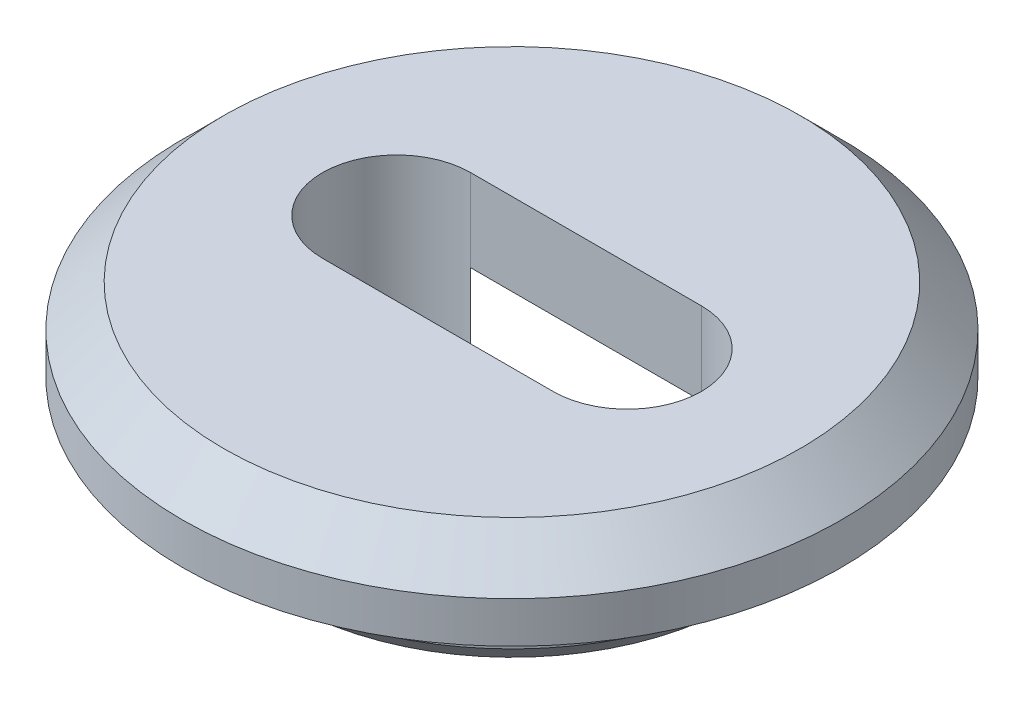
SolidWorks part; units mm, degrees
ref_plane "Front Plane" through (0, 0, 0) normal (0, 0, 1) x (1, 0, 0)
ref_plane "Top Plane" through (0, 0, 0) normal (0, 1, 0) x (1, 0, 0)
ref_plane "Right Plane" through (0, 0, 0) normal (1, 0, 0) x (0, 0, -1)
sketch "Sketch1" plane through (0, 0, 0) normal (0, 0, 1) x (1, 0, 0)
  line L0 (0, 0) -> (-8, 0)
  line L1 (-8, 0) -> (-8, -2)
  line L2 (-8, -2) -> (-6.1, -2)
  line L3 (-6.1, -2) -> (-6.1, -4)
  line L4 (-6.1, -4) -> (0, -4)
  line L5 (0, -4) -> (0, 0)
  line L6 (0, 0) -> (0, -10.029) construction
  dimension "D1" = 12.2
  dimension "D2" = 16
  dimension "D3" = 2
  dimension "D4" = 2
revolve "Revolve1" add sketch "Sketch1" angle 360 about L6
sketch "Sketch3" plane through (0, 0, 0) normal (0, 1, 0) x (1, 0, 0)
  line L0 (-2.8, 0) -> (2.8, 0) construction
  line L1 (-2.8, 1.8) -> (2.8, 1.8)
  line L2 (-2.8, -1.8) -> (2.8, -1.8)
  arc A0 (-2.8, 1.8) -> (-2.8, -1.8) centre (-2.8, 0) ccw
  arc A1 (2.8, -1.8) -> (2.8, 1.8) centre (2.8, 0) ccw
  point P2 (0, 0)
  dimension "D2" = 9.2
  dimension "D1" = 3.6
extrude "Cut-Extrude1" cut sketch "Sketch3" against normal through all
sketch "Sketch4" plane through (0, -4, 0) normal (0, -1, 0) x (1, 0, 0)
  line L0 (2.8, -1.8) -> (-2.8, -1.8) construction
  line L1 (-10.0418, -1.8) -> (11.1634, -1.8)
  line L2 (-10.0418, -1.8) -> (-10.0418, -3.6)
  line L3 (-10.0418, -3.6) -> (11.1634, -3.6)
  line L4 (11.1634, -1.8) -> (11.1634, -3.6)
  dimension "D1" = 1.8
extrude "Cut-Extrude2" cut sketch "Sketch4" against normal blind 2
sketch "Sketch5" plane through (0, -4, 0) normal (0, -1, 0) x (1, 0, 0)
  line L1 (-10.2288, -2.1496) -> (10.1665, -2.1496)
  line L2 (-10.2288, -2.1496) -> (-10.2288, -7.7988)
  line L3 (-10.2288, -7.7988) -> (10.1665, -7.7988)
  line L4 (10.1665, -2.1496) -> (10.1665, -7.7988)
extrude "Cut-Extrude3" cut sketch "Sketch5" against normal blind 1.4
chamfer "Chamfer1" distance 1 angle 45 1 edges at (0, 0, 8)
chamfer "Chamfer2" distance 0.6 angle 45 1 edges at (0, -4, 6.1)
